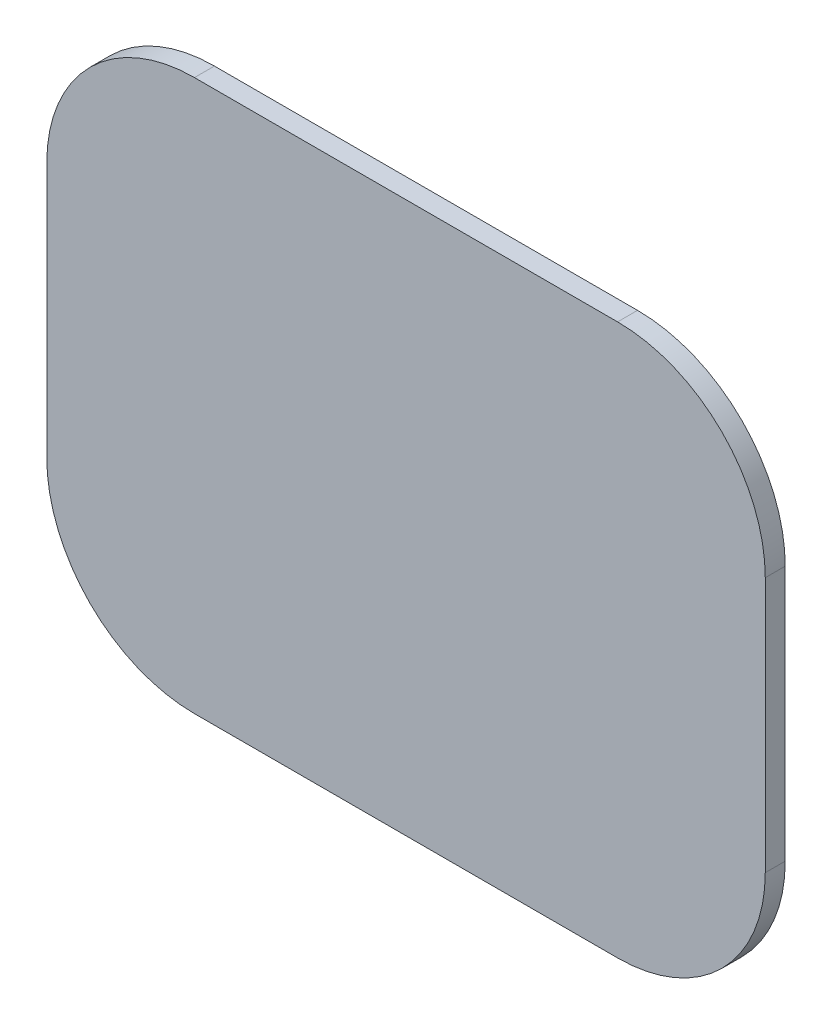
SolidWorks part; units mm, degrees
ref_plane "Front Plane" through (0, 0, 0) normal (0, 0, 1) x (1, 0, 0)
ref_plane "Top Plane" through (0, 0, 0) normal (0, 1, 0) x (1, 0, 0)
ref_plane "Right Plane" through (0, 0, 0) normal (1, 0, 0) x (0, 0, -1)
sketch "Sketch2" plane through (0, 0, -64.585) normal (0, 0, 1) x (1, 0, 0)
  line L4 (144.4809, 643.2506) -> (197.4809, 643.2506)
  line L5 (215.9809, 661.7506) -> (215.9809, 693.7506)
  line L6 (197.4809, 712.2506) -> (144.4809, 712.2506)
  line L7 (125.9809, 693.7506) -> (125.9809, 661.7506)
  line L8 (144.4809, 643.2506) -> (197.4809, 643.2506)
  line L9 (215.9809, 661.7506) -> (215.9809, 693.7506)
  line L10 (197.4809, 712.2506) -> (144.4809, 712.2506)
  line L11 (125.9809, 693.7506) -> (125.9809, 661.7506)
  line L16 (144.4809, 644.7506) -> (197.4809, 644.7506)
  line L17 (214.4809, 661.7506) -> (214.4809, 693.7506)
  line L18 (197.4809, 710.7506) -> (144.4809, 710.7506)
  line L19 (127.4809, 693.7506) -> (127.4809, 661.7506)
  line L20 (144.4809, 644.7506) -> (197.4809, 644.7506)
  line L21 (214.4809, 661.7506) -> (214.4809, 693.7506)
  line L22 (197.4809, 710.7506) -> (144.4809, 710.7506)
  line L23 (127.4809, 693.7506) -> (127.4809, 661.7506)
  arc A4 (125.9809, 661.7506) -> (144.4809, 643.2506) centre (144.4809, 661.7506) ccw
  arc A5 (197.4809, 643.2506) -> (215.9809, 661.7506) centre (197.4809, 661.7506) ccw
  arc A6 (215.9809, 693.7506) -> (197.4809, 712.2506) centre (197.4809, 693.7506) ccw
  arc A7 (144.4809, 712.2506) -> (125.9809, 693.7506) centre (144.4809, 693.7506) ccw
  arc A8 (125.9809, 661.7506) -> (144.4809, 643.2506) centre (144.4809, 661.7506) ccw
  arc A9 (197.4809, 643.2506) -> (215.9809, 661.7506) centre (197.4809, 661.7506) ccw
  arc A10 (215.9809, 693.7506) -> (197.4809, 712.2506) centre (197.4809, 693.7506) ccw
  arc A11 (144.4809, 712.2506) -> (125.9809, 693.7506) centre (144.4809, 693.7506) ccw
  arc A16 (127.4809, 661.7506) -> (144.4809, 644.7506) centre (144.4809, 661.7506) ccw
  arc A17 (197.4809, 644.7506) -> (214.4809, 661.7506) centre (197.4809, 661.7506) ccw
  arc A18 (214.4809, 693.7506) -> (197.4809, 710.7506) centre (197.4809, 693.7506) ccw
  arc A19 (144.4809, 710.7506) -> (127.4809, 693.7506) centre (144.4809, 693.7506) ccw
  arc A20 (127.4809, 661.7506) -> (144.4809, 644.7506) centre (144.4809, 661.7506) ccw
  arc A21 (197.4809, 644.7506) -> (214.4809, 661.7506) centre (197.4809, 661.7506) ccw
  arc A22 (214.4809, 693.7506) -> (197.4809, 710.7506) centre (197.4809, 693.7506) ccw
  arc A23 (144.4809, 710.7506) -> (127.4809, 693.7506) centre (144.4809, 693.7506) ccw
  dimension "D1" = 0
  dimension "D2" = 1.5
extrude "Boss-Extrude1" add sketch "Sketch2" along normal offset from surface (71.585 mm away) 2
sketch "Sketch3" plane through (0, 0, 7) normal (0, 0, 1) x (1, 0, 0)
  line L4 (125.9809, 693.7506) -> (125.9809, 661.7506)
  line L5 (144.4809, 643.2506) -> (197.4809, 643.2506)
  line L6 (215.9809, 661.7506) -> (215.9809, 693.7506)
  line L7 (197.4809, 712.2506) -> (144.4809, 712.2506)
  line L8 (125.9809, 693.7506) -> (125.9809, 661.7506)
  line L9 (144.4809, 643.2506) -> (197.4809, 643.2506)
  line L10 (215.9809, 661.7506) -> (215.9809, 693.7506)
  line L11 (197.4809, 712.2506) -> (144.4809, 712.2506)
  arc A4 (125.9809, 661.7506) -> (144.4809, 643.2506) centre (144.4809, 661.7506) ccw
  arc A5 (197.4809, 643.2506) -> (215.9809, 661.7506) centre (197.4809, 661.7506) ccw
  arc A6 (215.9809, 693.7506) -> (197.4809, 712.2506) centre (197.4809, 693.7506) ccw
  arc A7 (144.4809, 712.2506) -> (125.9809, 693.7506) centre (144.4809, 693.7506) ccw
  arc A8 (125.9809, 661.7506) -> (144.4809, 643.2506) centre (144.4809, 661.7506) ccw
  arc A9 (197.4809, 643.2506) -> (215.9809, 661.7506) centre (197.4809, 661.7506) ccw
  arc A10 (215.9809, 693.7506) -> (197.4809, 712.2506) centre (197.4809, 693.7506) ccw
  arc A11 (144.4809, 712.2506) -> (125.9809, 693.7506) centre (144.4809, 693.7506) ccw
  dimension "D1" = 0
extrude "Boss-Extrude2" add sketch "Sketch3" along normal blind 2.5
